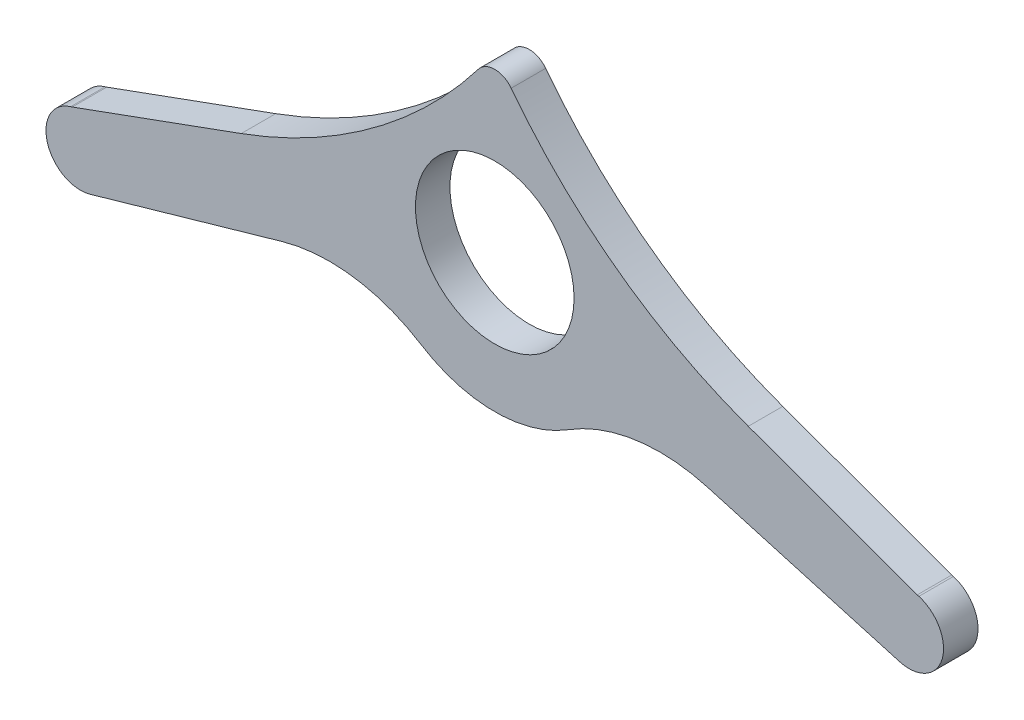
SolidWorks part; units mm, degrees
ref_plane "Front Plane" through (0, 0, 0) normal (0, 0, 1) x (1, 0, 0)
ref_plane "Top Plane" through (0, 0, 0) normal (0, 1, 0) x (1, 0, 0)
ref_plane "Right Plane" through (0, 0, 0) normal (1, 0, 0) x (0, 0, -1)
sketch "Sketch1" plane through (0, 0, 0) normal (0, 0, 1) x (1, 0, 0)
  line L0 (20, 0) -> (62.5, 0)
  line L1 (19.2252, -5.5127) -> (60.0789, -17.2273)
  line L2 (61.5023, -12.4342) -> (61.2649, -12.3637)
  line L3 (0, 0) -> (0, 20)
  line L4 (19.2252, -5.5127) -> (60.0789, -17.2273)
  line L5 (58.7007, -22.0336) -> (30.8635, -14.0515)
  line L6 (-58.7007, -22.0336) -> (-58.5081, -21.9784)
  line L7 (-61.5023, -12.4342) -> (-61.2649, -12.3637)
  line L8 (61.2649, -12.3637) -> (36.7614, -3.4452)
  line L10 (-58.7007, -22.0336) -> (-30.8635, -14.0515)
  line L11 (-61.2649, -12.3637) -> (-36.7614, -3.4452)
  line L12 (-19.2252, -5.5127) -> (-60.0789, -17.2273)
  circle A0 centre (0, 0) radius 11.5
  arc A1 (-19.1655, 5.7168) -> (19.1655, 5.7168) centre (0, 0) ccw
  circle A4 centre (0, 20) radius 3
  arc A5 (-58.5095, -21.9747) -> (-61.2637, -12.3697) centre (0, 0) ccw construction
  circle A6 centre (60.0789, -17.2273) radius 5
  arc A7 (36.7614, -3.4452) -> (2.3842, 21.8209) centre (62.7336, 67.9127) cw
  arc A8 (30.8635, -14.0515) -> (10.6545, -16.9258) centre (23.9726, -38.083) ccw
  arc A9 (-58.5095, -21.9747) -> (-58.7007, -22.0336) centre (-60.0789, -17.2273) cw
  arc A10 (-61.5023, -12.4342) -> (-61.2637, -12.3697) centre (-60.0789, -17.2273) cw
  arc A11 (-30.8635, -14.0515) -> (-10.6545, -16.9258) centre (-23.9726, -38.083) cw
  circle A12 centre (-60.0789, -17.2273) radius 5
  arc A13 (-36.7614, -3.4452) -> (-2.3842, 21.8209) centre (-62.7336, 67.9127) ccw
  arc A14 (4.1817, 19.5579) -> (-4.1817, 19.5579) centre (0, 0) ccw
  dimension "D1" = 23
  dimension "D2" = 40
  dimension "D3" = 16
  dimension "D4" = 6
  dimension "D5" = 62.5
  dimension "D6" = 10
  dimension "D7" = 4
  dimension "D8" = 25
extrude "Boss-Extrude2" add sketch "Sketch1" along normal blind 5
